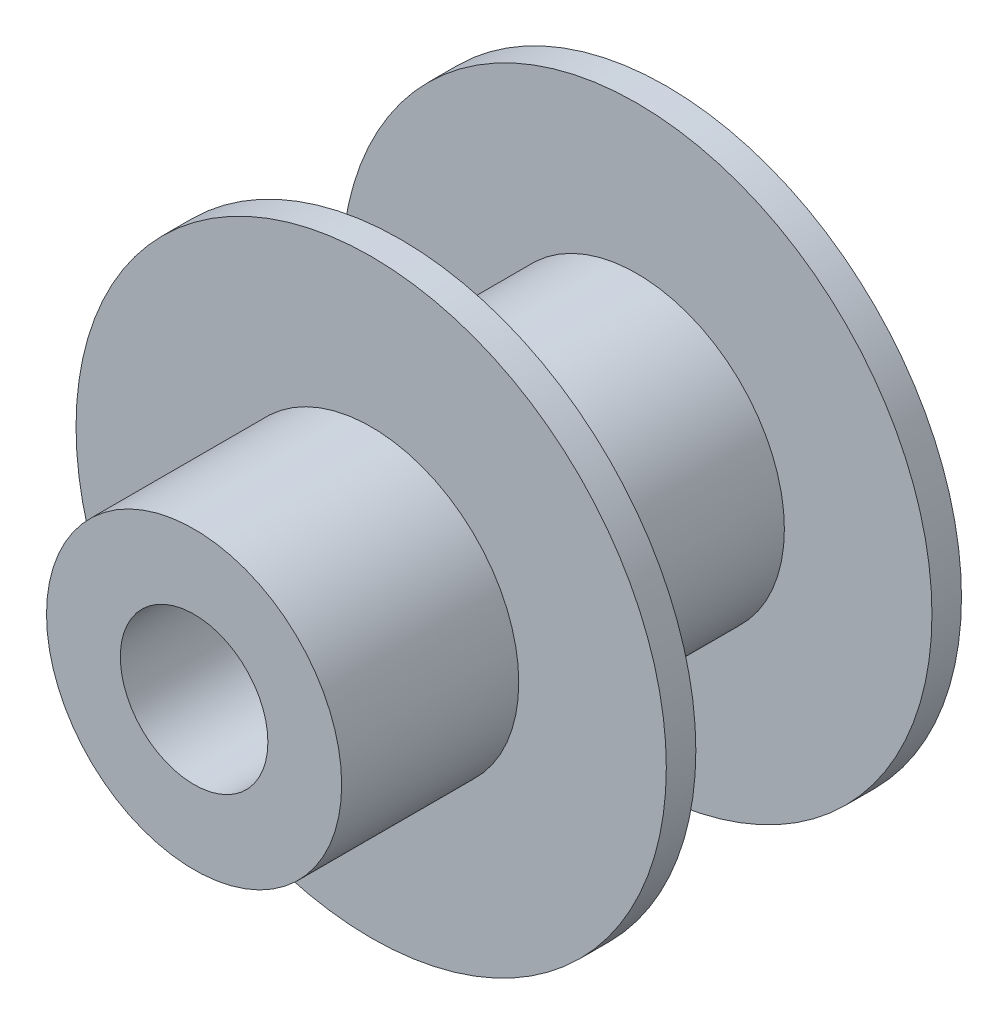
SolidWorks part; units mm, degrees
ref_plane "Plan de face" through (0, 0, 0) normal (0, 0, 1) x (1, 0, 0)
ref_plane "Plan de dessus" through (0, 0, 0) normal (0, 1, 0) x (1, 0, 0)
ref_plane "Plan de droite" through (0, 0, 0) normal (1, 0, 0) x (0, 0, -1)
sketch "Esquisse1" plane through (0, 0, 0) normal (0, 0, 1) x (1, 0, 0)
  circle A0 centre (0, 0) radius 10
  dimension "D1" = 20
extrude "Boss.-Extru.1" add sketch "Esquisse1" along normal blind 10
sketch "Esquisse2" plane through (0, 0, 10) normal (0, 0, 1) x (1, 0, 0)
  circle A0 centre (0, 0) radius 5
  dimension "D1" = 10
extrude "Boss.-Extru.2" add sketch "Esquisse2" along normal blind 6
sketch "Esquisse3" plane through (0, 0, 16) normal (0, 0, 1) x (1, 0, 0)
  circle A0 centre (0, 0) radius 2.5
  dimension "D1" = 5
extrude "Enlèv. mat.-Extru.1" cut sketch "Esquisse3" against normal through all
sketch "Esquisse4" plane through (0, 0, 0) normal (1, 0, 0) x (0, 0, -1)
  line L0 (0, 10) -> (-10, 10) construction
  line L1 (-1, 10) -> (-9, 10)
  line L2 (-1, 10) -> (-1, 5)
  line L3 (-1, 5) -> (-9, 5)
  line L4 (-9, 10) -> (-9, 5)
  line L5 (-10, 10) -> (-10, -10) construction
  line L6 (0, -10) -> (0, 10) construction
  line L7 (0, 0) -> (-3.6877, 0) construction
  dimension "D1" = 1
  dimension "D2" = 1
  dimension "D3" = 5
revolve "Enlèvement de matière-Révolution1" cut sketch "Esquisse4" angle 360 about L7
